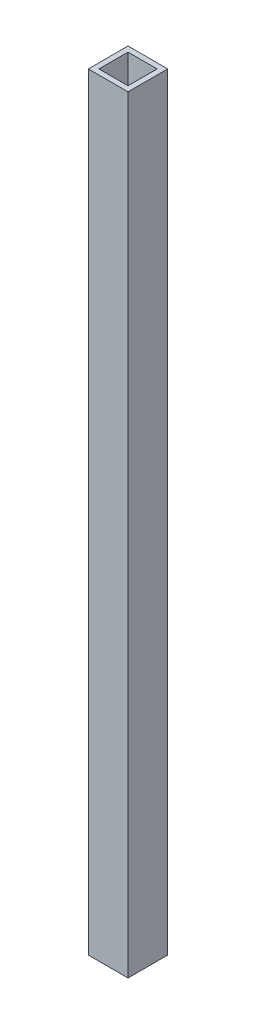
SolidWorks part; units mm, degrees
ref_plane "Front Plane" through (0, 0, 0) normal (0, 0, 1) x (1, 0, 0)
ref_plane "Top Plane" through (0, 0, 0) normal (0, 1, 0) x (1, 0, 0)
ref_plane "Right Plane" through (0, 0, 0) normal (1, 0, 0) x (0, 0, -1)
sketch "Sketch1" plane through (0, 0, 0) normal (0, 1, 0) x (1, 0, 0)
  line L0 (2, 2) -> (2, 13)
  line L1 (0, 0) -> (15, 0)
  line L2 (0, 0) -> (0, 15)
  line L3 (0, 15) -> (15, 15)
  line L4 (15, 0) -> (15, 15)
  line L5 (2, 13) -> (13, 13)
  line L6 (13, 2) -> (13, 13)
  line L7 (2, 2) -> (13, 2)
  dimension "D1" = 15
  dimension "D2" = 2
extrude "Boss-Extrude1" add sketch "Sketch1" along normal blind 290
